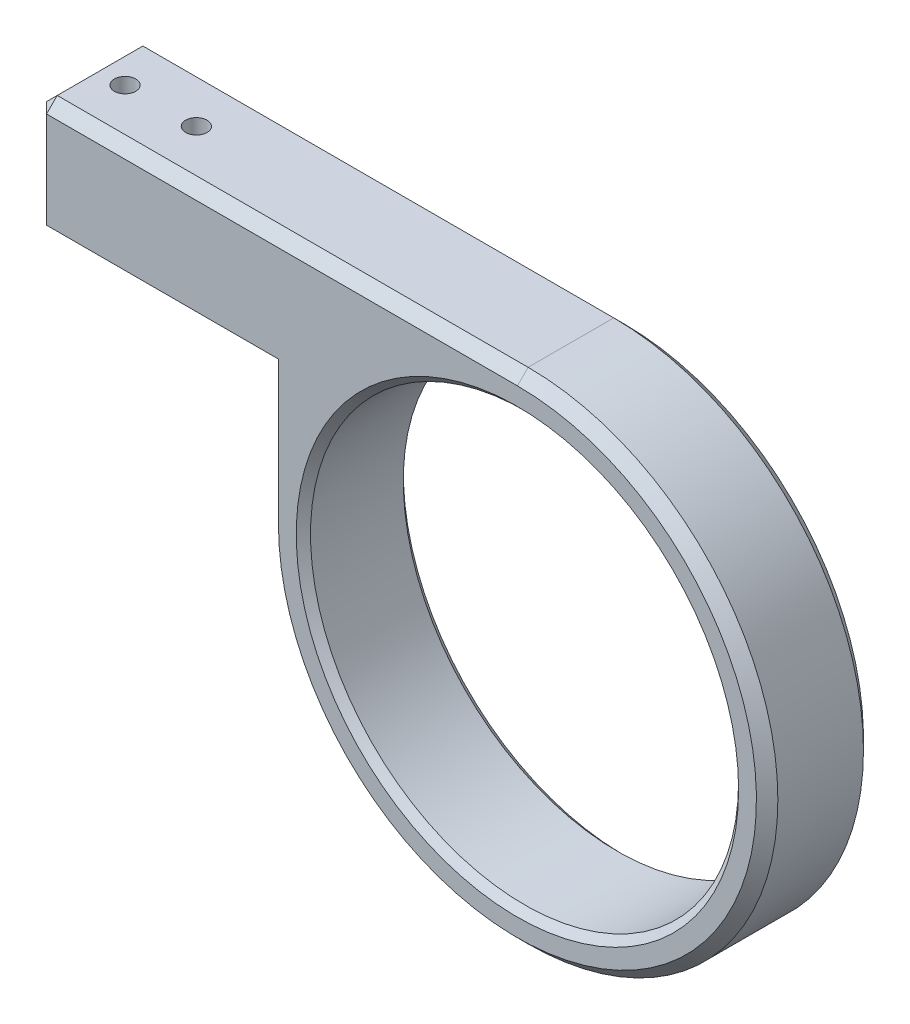
SolidWorks part; units mm, degrees
ref_plane "Front" through (0, 0, 0) normal (0, 0, 1) x (1, 0, 0)
ref_plane "Top" through (0, 0, 0) normal (0, 1, 0) x (1, 0, 0)
ref_plane "Right" through (0, 0, 0) normal (1, 0, 0) x (0, 0, -1)
sketch "草图1" plane through (0, 0, 0) normal (0, 0, 1) x (1, 0, 0)
  circle A0 centre (0, 0) radius 35
  dimension "D1" = 70
extrude "凸台-拉伸1" add sketch "草图1" along normal blind 15
sketch "草图2" plane through (0, 0, 0) normal (0, 0, -1) x (-1, 0, 0)
  circle A0 centre (0, 0) radius 30
  dimension "D1" = 60
extrude "切除-拉伸1" cut sketch "草图2" against normal through all
ref_plane "基准面1" through (-35, 0, 0) normal (-1, 0, 0) x (0, 0, 1)
sketch "草图3" plane through (-35, 0, 0) normal (-1, 0, 0) x (0, 0, 1)
  line L0 (0, 35) -> (0, -35) construction
  line L1 (15, 20) -> (0, 20)
  line L2 (15, 20) -> (15, 35)
  line L3 (15, 35) -> (0, 35)
  line L4 (0, 20) -> (0, 35)
  line L5 (15, 20) -> (0, 35) construction
  line L6 (15, 35) -> (0, 20) construction
  line L7 (15, -35) -> (15, 35) construction
  line L8 (0, 0) -> (15, 0) construction
  point P0 (7.5, 27.5)
  point P12 (0, 0)
  dimension "D1" = 20
  dimension "D2" = 15
extrude "凸台-拉伸2" add sketch "草图3" against normal up to surface (6.2772 mm away)
sketch "草图4" plane through (-35, 0, 0) normal (-1, 0, 0) x (0, 0, 1)
  line L0 (15, 35) -> (0, 35) construction
  line L1 (15, 20) -> (0, 20)
  line L2 (15, 20) -> (15, 35)
  line L3 (15, 35) -> (0, 35)
  line L4 (0, 20) -> (0, 35)
  line L5 (15, 20) -> (0, 35) construction
  line L6 (15, 35) -> (0, 20) construction
  line L7 (0, 35) -> (0, 20) construction
  line L8 (15, 20) -> (15, 35) construction
  line L9 (0, 20) -> (15, 20) construction
  point P0 (7.5, 27.5)
extrude "凸台-拉伸3" add sketch "草图4" along normal blind 32.5
sketch "草图6" plane through (-35, 0, 0) normal (-1, 0, 0) x (0, 0, 1)
  line L1 (15, 0) -> (0, 0)
  line L2 (15, 0) -> (15, 20)
  line L3 (15, 20) -> (0, 20)
  line L4 (0, 0) -> (0, 20)
  line L5 (15, 0) -> (0, 20) construction
  line L6 (15, 20) -> (0, 0) construction
  line L7 (0, 20) -> (15, 20) construction
  line L8 (0, 35) -> (0, -35) construction
  line L9 (15, -35) -> (15, 35) construction
  line L10 (0, 0) -> (15, 0) construction
  point P0 (7.5, 10)
  point P14 (0, 0)
extrude "凸台-拉伸4" add sketch "草图6" against normal up to surface up to face at (0.9202, -1.7621, 7.5)
sketch "草图7" plane through (0, 20, 0) normal (0, -1, 0) x (1, 0, 0)
  line L0 (-67.5, 7.5) -> (-35, 7.5) construction
  line L1 (-67.5, 0) -> (-67.5, 15) construction
  line L2 (-35, 15) -> (-35, 0) construction
  circle A0 centre (-62.5, 7.5) radius 1.5
  circle A1 centre (-52.5, 7.5) radius 1.5
  dimension "D1" = 3
  dimension "D2" = 3
  dimension "D3" = 5
  dimension "D4" = 10
extrude "切除-拉伸2" cut sketch "草图7" against normal through all
chamfer "倒角1" distance 1 angle 45 2 edges at (-30, 0, 15) (-30, 0, 0)
chamfer "倒角2" distance 1.5 angle 45 9 edges at (-67.5, 27.5, 15) (-67.5, 27.5, 0) (-35, 10, 0) (-33.75, 35, 0) (24.7487, -24.7487, 15) (24.7487, -24.7487, 0) (-35, 10, 15) (-33.75, 35, 15) (-67.5, 35, 7.5)
